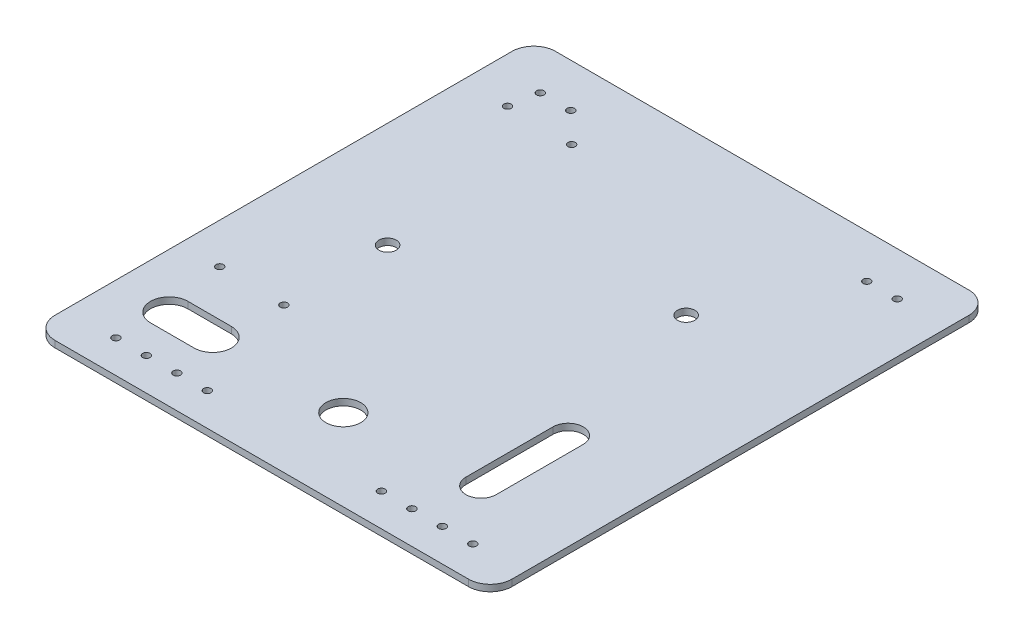
SolidWorks part; units mm, degrees
ref_plane "Front Plane" through (0, 0, 0) normal (0, 0, 1) x (1, 0, 0)
ref_plane "Top Plane" through (0, 0, 0) normal (0, 1, 0) x (1, 0, 0)
ref_plane "Right Plane" through (0, 0, 0) normal (1, 0, 0) x (0, 0, -1)
sketch "Sketch1" plane through (0, 0, 0) normal (0, 1, 0) x (1, 0, 0)
  line L1 (-105, 140) -> (105, 140)
  line L2 (-105, 140) -> (-105, -90)
  line L3 (-105, -90) -> (105, -90)
  line L4 (105, 140) -> (105, -90)
  line L5 (-105, 140) -> (105, -90) construction
  line L6 (-105, -90) -> (105, 140) construction
  point P0 (0, 25)
  dimension "D1" = 230
  dimension "D2" = 210
  dimension "D3" = 25
extrude "Boss-Extrude1" add sketch "Sketch1" along normal blind 3
fillet "Fillet1" radius 10 4 edges at (-105, 1.5, -140) (-105, 1.5, 90) (105, 1.5, -140) (105, 1.5, 90)
sketch "Sketch2" plane through (0, 3, 0) normal (0, 1, 0) x (1, 0, 0)
  circle A0 centre (-82, 120) radius 1.7
  circle A1 centre (-68, 120) radius 1.7
  circle A2 centre (68, 120) radius 1.7
  circle A3 centre (82, 120) radius 1.7
  circle A4 centre (-82, -75) radius 1.7
  circle A5 centre (-68, -75) radius 1.7
  circle A6 centre (68, -75) radius 1.7
  circle A7 centre (82, -75) radius 1.7
  circle A32 centre (-54, -75) radius 1.7
  circle A33 centre (54, -75) radius 1.7
  circle A34 centre (-40, -75) radius 1.7
  circle A35 centre (40, -75) radius 1.7
  dimension "D1" = 3.4
  dimension "D11" = 14
  dimension "D18" = 14
  dimension "D19" = 14
  dimension "D20" = 14
  dimension "D2" = 14
  dimension "D3" = 14
  dimension "D4" = 82
  dimension "D5" = 82
  dimension "D6" = 120
  dimension "D7" = 75
extrude "Cut-Extrude1" cut sketch "Sketch2" against normal up to surface (3 mm away) up to face at (0, 0, -25)
sketch "Sketch3" plane through (0, 3, 0) normal (0, 1, 0) x (1, 0, 0)
  circle A0 centre (40, 65) radius 4
  dimension "D1" = 8
  dimension "D2" = 40
  dimension "D3" = 65
extrude "Cut-Extrude2" cut sketch "Sketch3" against normal through all
sketch "Sketch4" plane through (0, 3, 0) normal (0, 1, 0) x (1, 0, 0)
  circle A0 centre (0, -52.5) radius 8
  dimension "D2" = 16
  dimension "D1" = 52.5
extrude "Cut-Extrude3" cut sketch "Sketch4" against normal through all
sketch "Sketch5" plane through (0, 3, 0) normal (0, 1, 0) x (1, 0, 0)
  line L0 (60.792, -10) -> (60.792, -50) construction
  line L1 (67.7571, -10) -> (67.7571, -50)
  line L2 (53.8268, -10) -> (53.8268, -50)
  line L3 (-80, -52.5) -> (-60, -52.5) construction
  line L4 (-80, -43.9213) -> (-60, -43.9213)
  line L5 (-80, -61.0787) -> (-60, -61.0787)
  arc A0 (67.7571, -10) -> (53.8268, -10) centre (60.792, -10) ccw
  arc A1 (53.8268, -50) -> (67.7571, -50) centre (60.792, -50) ccw
  arc A2 (-80, -43.9213) -> (-80, -61.0787) centre (-80, -52.5) ccw
  arc A3 (-60, -61.0787) -> (-60, -43.9213) centre (-60, -52.5) ccw
  point P2 (60.792, -30)
  point P7 (-70, -52.5)
  dimension "D1" = 20
  dimension "D2" = 70
  dimension "D3" = 30
  dimension "D4" = 40
extrude "Cut-Extrude4" cut sketch "Sketch5" against normal through all
sketch "Sketch6" plane through (0, 3, 0) normal (0, 1, 0) x (1, 0, 0)
  circle A0 centre (-56.482, 24.3143) radius 4
  circle A1 centre (-84.2111, 107.1437) radius 1.7
  circle A2 centre (-54.2155, 106.6275) radius 1.7
  circle A3 centre (-56.4526, -23.3533) radius 1.7
  circle A4 centre (-86.4482, -22.837) radius 1.7
extrude "Cut-Extrude5" cut sketch "Sketch6" against normal through all
